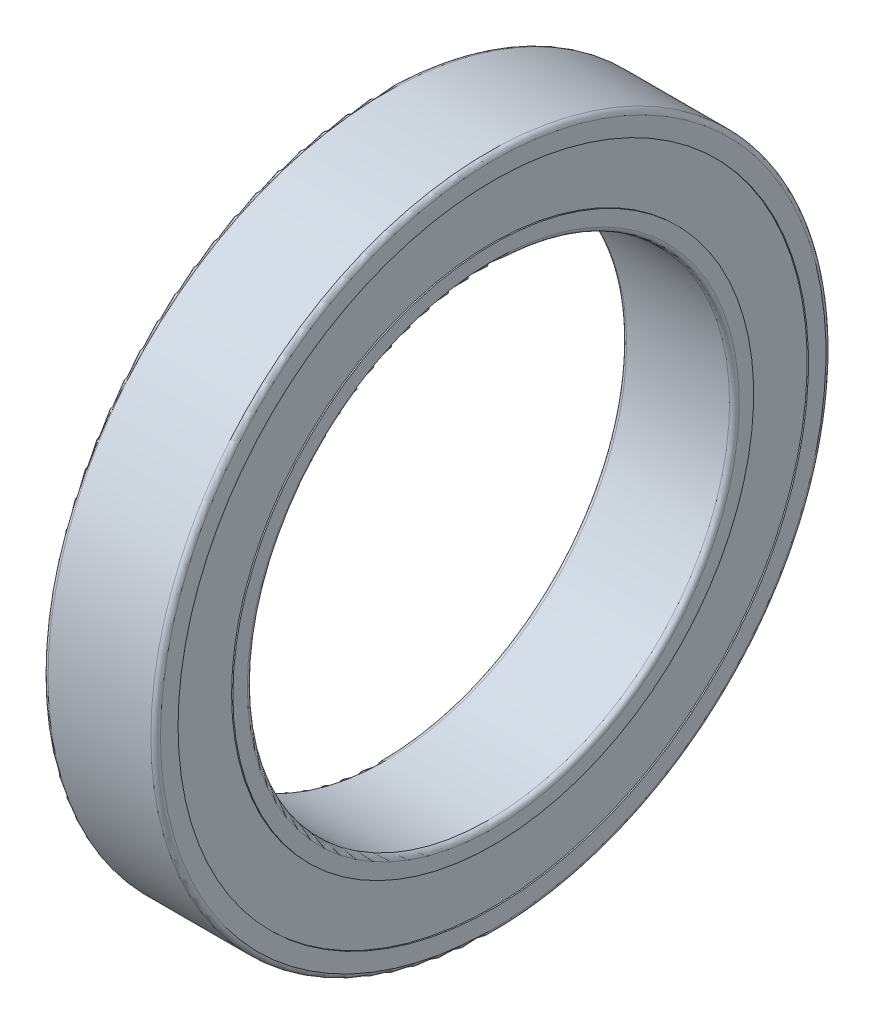
SolidWorks part; units mm, degrees
material "1.4301 (X5CrNi18-10)"
ref_plane "正面" through (0, 0, 0) normal (0, 0, 1) x (1, 0, 0)
ref_plane "平面" through (0, 0, 0) normal (0, 1, 0) x (1, 0, 0)
ref_plane "右側面" through (0, 0, 0) normal (1, 0, 0) x (0, 0, -1)
sketch "ｽｹｯﾁ1" plane through (0, 0, 0) normal (0, 0, 1) x (1, 0, 0)
  line L0 (0, 0) -> (33211.2791, 0) construction
  line L1 (-3.2, 21) -> (3.2, 21)
  line L2 (3.5, 20.7) -> (3.5, 19.61)
  line L3 (3.5, 19.61) -> (3.178, 19.61)
  line L4 (3.178, 19.61) -> (3.178, 19.1)
  line L5 (3.178, 19.1) -> (1.0198, 19.1)
  line L6 (0, 21) -> (0, 0) construction
  line L7 (-1.0198, 19.1) -> (-3.178, 19.1)
  line L8 (-3.178, 16.7) -> (-0.7483, 16.7)
  line L9 (3.5, 16.2) -> (3.5, 15.3)
  line L10 (3.2, 15) -> (-3.2, 15)
  line L11 (-3.5, 16.2) -> (-3.5, 15.3)
  line L12 (-3.178, 19.61) -> (-3.178, 19.1)
  line L13 (-3.5, 19.61) -> (-3.178, 19.61)
  line L14 (-3.5, 20.7) -> (-3.5, 19.61)
  line L15 (0.7483, 16.7) -> (3.178, 16.7)
  line L16 (3.178, 16.7) -> (3.178, 16.2)
  line L17 (3.178, 16.2) -> (3.5, 16.2)
  line L18 (-3.178, 16.7) -> (-3.178, 16.2)
  line L19 (-3.178, 16.2) -> (-3.5, 16.2)
  arc A0 (-0.7483, 16.7) -> (0.7483, 16.7) centre (0, 18) ccw
  arc A1 (1.0198, 19.1) -> (-1.0198, 19.1) centre (0, 18) ccw
  arc A2 (-3.5, 15.3) -> (-3.2, 15) centre (-3.2, 15.3) ccw
  arc A3 (3.2, 21) -> (3.5, 20.7) centre (3.2, 20.7) cw
  arc A4 (-3.2, 21) -> (-3.5, 20.7) centre (-3.2, 20.7) ccw
  arc A5 (3.5, 15.3) -> (3.2, 15) centre (3.2, 15.3) cw
  point P28 (-3.5, 15)
  point P31 (3.5, 21)
  point P34 (-3.5, 21)
  point P37 (3.5, 15)
  dimension "D8" = 3
  dimension "D10" = 32.4
  dimension "D11" = 0.3
  dimension "D1" = 42
  dimension "D2" = 33.4
  dimension "D3" = 38.2
  dimension "D4" = 30
  dimension "D5" = 7
  dimension "D6" = 39.22
  dimension "D7" = 0.322
  dimension "D9" = 36
revolve "回転1" add sketch "ｽｹｯﾁ1" angle 360 about L0
sketch "ｽｹｯﾁ3" plane through (0, 0, 0) normal (0, 0, 1) x (1, 0, 0)
  line L0 (3.178, 19.61) -> (3.178, 16.2)
  line L2 (3.178, 16.2) -> (3.4195, 16.2)
  line L3 (3.4195, 16.2) -> (3.4195, 19.61)
  line L4 (3.4195, 19.61) -> (3.178, 19.61)
  line L5 (0, 0) -> (0, -50000) construction
  line L6 (-3.4195, 19.61) -> (-3.178, 19.61)
  line L7 (-3.4195, 16.2) -> (-3.4195, 19.61)
  line L8 (-3.178, 16.2) -> (-3.4195, 16.2)
  line L9 (-3.178, 19.61) -> (-3.178, 16.2)
  line L10 (3.178, 16.2) -> (3.5, 16.2) construction
  dimension "D1" = 0.2415
revolve "回転3" add sketch "ｽｹｯﾁ3" angle 360 about L0
sketch "ｽｹｯﾁ2" plane through (0, 0, 0) normal (0, 0, 1) x (1, 0, 0)
  line L0 (0.0469, 18) -> (50000.0469, 18) construction
  line L1 (-1.5, 18) -> (1.5, 18)
  arc A0 (1.5, 18) -> (-1.5, 18) centre (0, 18) ccw
  dimension "D1" = 3
revolve "回転2" add sketch "ｽｹｯﾁ2" angle 360 about L0
pattern_circular "円形ﾊﾟﾀｰﾝ2" count 13 over 360 about axis through (0, 0, 0) along (1, 0, 0) of bodies 103
